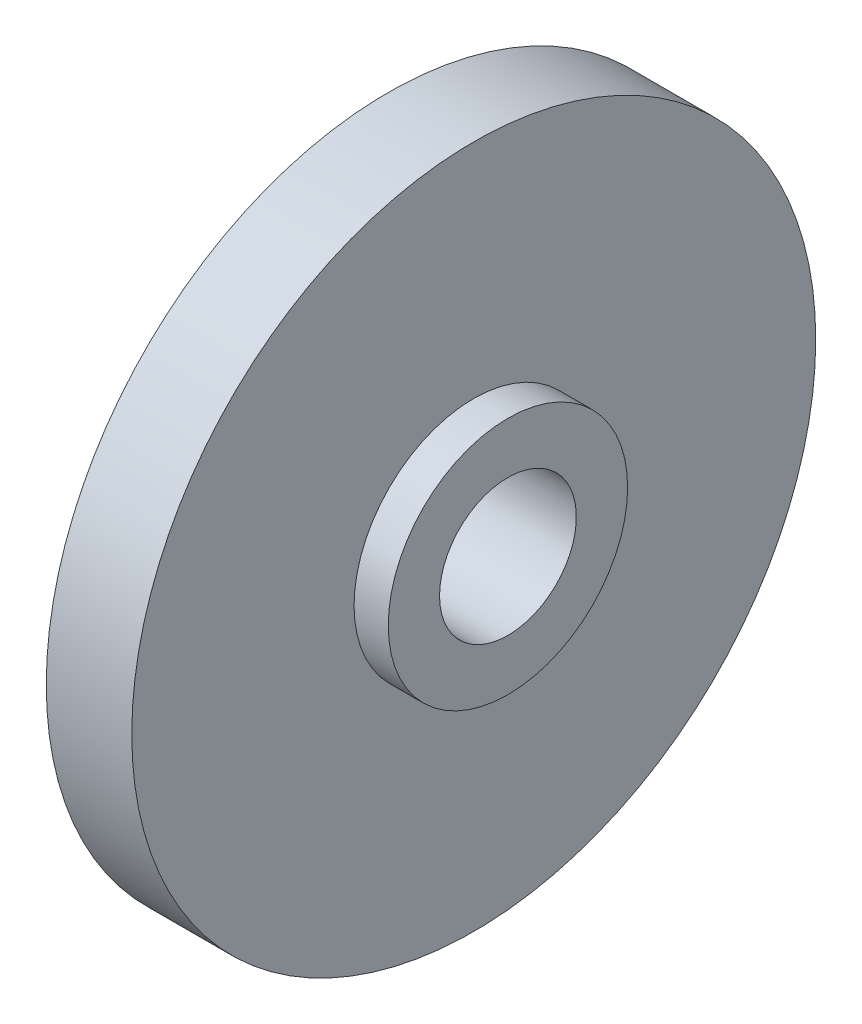
SolidWorks part; units mm, degrees
ref_plane "Front" through (0, 0, 0) normal (0, 0, 1) x (1, 0, 0)
ref_plane "Top" through (0, 0, 0) normal (0, 1, 0) x (1, 0, 0)
ref_plane "Right" through (0, 0, 0) normal (1, 0, 0) x (0, 0, -1)
sketch "Esquisse1" plane through (0, 0, 0) normal (0, 0, 1) x (1, 0, 0)
  line L0 (0, 5.7467) -> (0, 20)
  line L1 (0, 0) -> (5, 0) construction
  line L2 (0, 0) -> (0, 20) construction
  line L3 (0, 20) -> (5, 20) construction
  line L4 (5, 0) -> (5, 20) construction
  line L5 (0, 20) -> (5, 20)
  line L6 (5, 20) -> (5, 7)
  line L7 (5, 7) -> (7, 7)
  line L8 (7, 7) -> (7, 4)
  line L9 (7, 4) -> (0, 4)
  line L10 (0, 4) -> (0, 5.7467)
  point P7 (0, 5.7467)
  point P11 (0, 0)
  dimension "D1" = 5
  dimension "D2" = 20
  dimension "D3" = 7
  dimension "D4" = 7
  dimension "D5" = 4
revolve "Révolution1" add sketch "Esquisse1" angle 360 about L1
